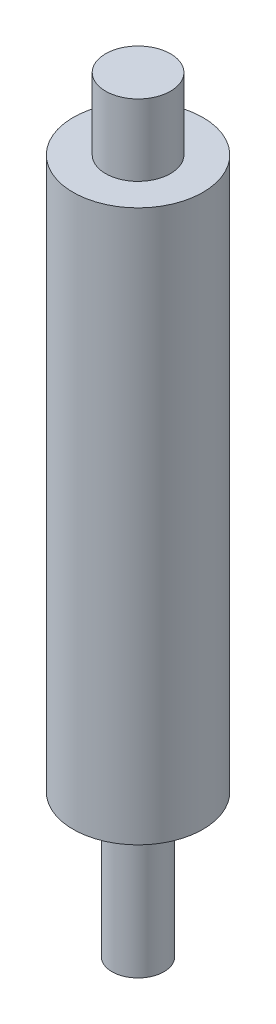
SolidWorks part; units mm, degrees
ref_plane "Alzado" through (0, 0, 0) normal (0, 0, 1) x (1, 0, 0)
ref_plane "Planta" through (0, 0, 0) normal (0, 1, 0) x (1, 0, 0)
ref_plane "Vista lateral" through (0, 0, 0) normal (1, 0, 0) x (0, 0, -1)
sketch "Croquis1" plane through (0, 0, 0) normal (0, 0, 1) x (1, 0, 0)
  line L0 (0, 0) -> (0, 118)
  line L1 (0, 118) -> (-5, 118)
  line L2 (-5, 118) -> (-5, 107)
  line L3 (-5, 107) -> (-10, 107)
  line L4 (-10, 107) -> (-10, 22)
  line L5 (-10, 22) -> (-4, 22)
  line L6 (-4, 22) -> (-4, 0)
  line L7 (-4, 0) -> (0, 0)
  dimension "D1" = 5
  dimension "D2" = 4
  dimension "D3" = 10
  dimension "D4" = 85
  dimension "D5" = 22
  dimension "D6" = 118
revolve "Revolución1" add sketch "Croquis1" angle 360 about L0
